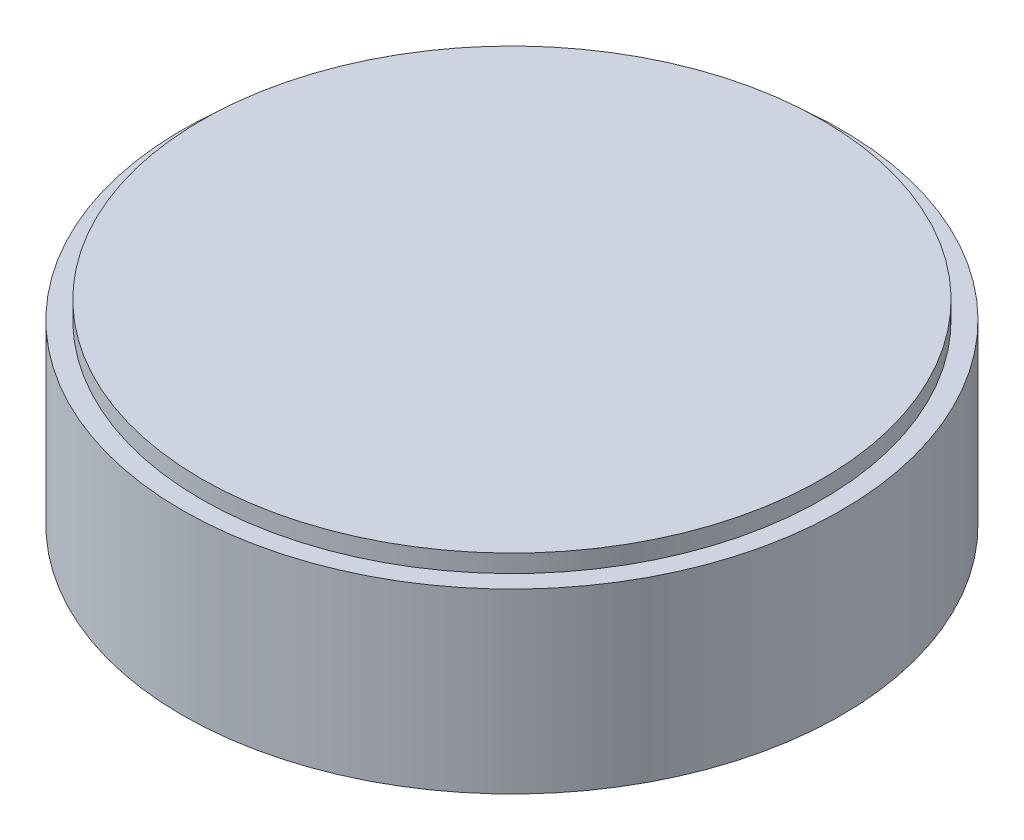
SolidWorks part; units mm, degrees
ref_plane "Front Plane" through (0, 0, 0) normal (0, 0, 1) x (1, 0, 0)
ref_plane "Top Plane" through (0, 0, 0) normal (0, 1, 0) x (1, 0, 0)
ref_plane "Right Plane" through (0, 0, 0) normal (1, 0, 0) x (0, 0, -1)
sketch "Sketch1" plane through (0, 0, 0) normal (0, 1, 0) x (1, 0, 0)
  circle A0 centre (-8.0556, 10.7407) radius 17.5
  circle A1 centre (-8.0556, 10.7407) radius 18.5728
  dimension "D1" = 35
extrude "Boss-Extrude1" add sketch "Sketch1" along normal blind 10
sketch "Sketch2" plane through (0, 10, 0) normal (0, 1, 0) x (1, 0, 0)
  circle A0 centre (-8.0556, 10.7407) radius 17.5
extrude "Boss-Extrude2" add sketch "Sketch2" along normal blind 1 separate body
